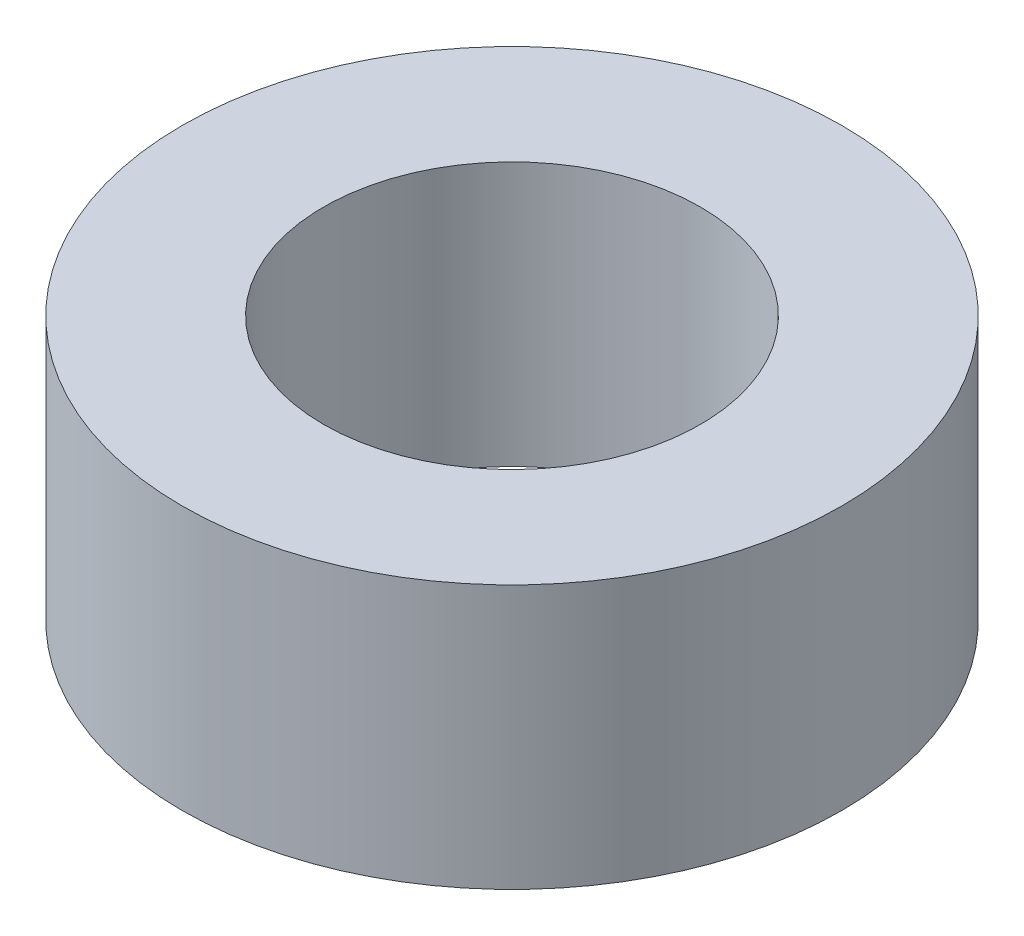
SolidWorks part; units mm, degrees
ref_plane "Front Plane" through (0, 0, 0) normal (0, 0, 1) x (1, 0, 0)
ref_plane "Top Plane" through (0, 0, 0) normal (0, 1, 0) x (1, 0, 0)
ref_plane "Right Plane" through (0, 0, 0) normal (1, 0, 0) x (0, 0, -1)
sketch "Sketch1" plane through (0, 0, 0) normal (0, 1, 0) x (1, 0, 0)
  circle A0 centre (0, 0) radius 2
  circle A1 centre (0, 0) radius 3.5
  dimension "D1" = 4
  dimension "D2" = 7
extrude "Boss-Extrude1" add sketch "Sketch1" along normal blind 2.8
